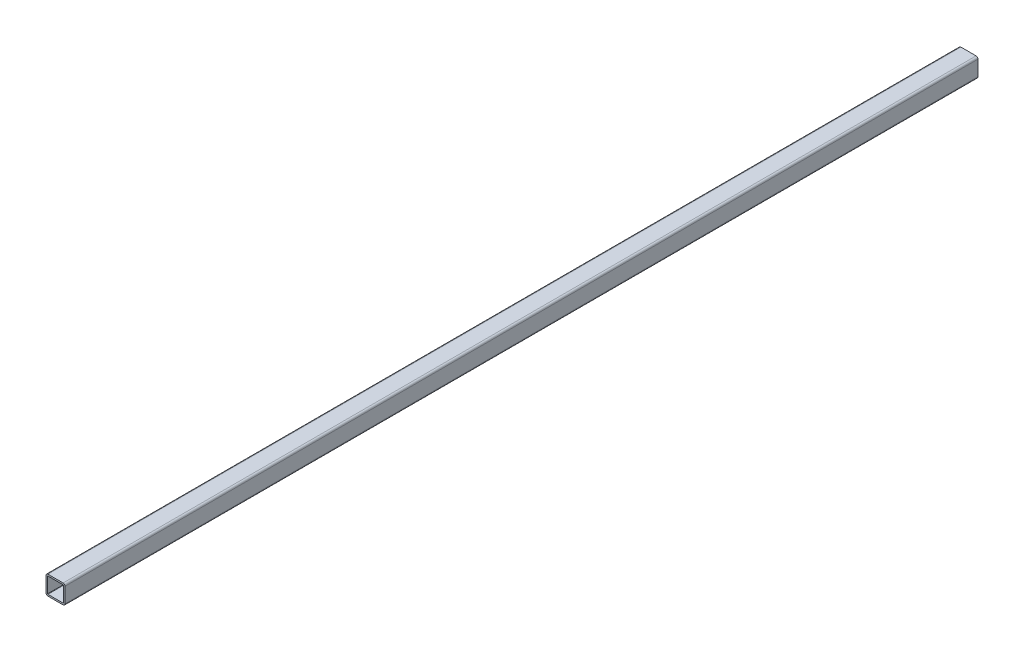
SolidWorks part; units mm, degrees
ref_plane "Front Plane" through (0, 0, 0) normal (0, 0, 1) x (1, 0, 0)
ref_plane "Top Plane" through (0, 0, 0) normal (0, 1, 0) x (1, 0, 0)
ref_plane "Right Plane" through (0, 0, 0) normal (1, 0, 0) x (0, 0, -1)
sketch "Sketch1" plane through (0, 0, 0) normal (0, 0, 1) x (1, 0, 0)
  line L0 (7.9375, -7.9375) -> (9.525, -7.9375) construction
  line L1 (-9.525, -9.525) -> (9.525, -9.525)
  line L2 (-9.525, -9.525) -> (-9.525, 9.525)
  line L3 (-9.525, 9.525) -> (9.525, 9.525)
  line L4 (9.525, -9.525) -> (9.525, 9.525)
  line L5 (0, 9.525) -> (0, -9.525) construction
  line L6 (-9.525, 0) -> (9.525, 0) construction
  line L7 (-7.9375, -7.9375) -> (7.9375, -7.9375)
  line L8 (-7.9375, -7.9375) -> (-7.9375, 7.9375)
  line L9 (-7.9375, 7.9375) -> (7.9375, 7.9375)
  line L10 (7.9375, -7.9375) -> (7.9375, 7.9375)
  line L11 (0, 7.9375) -> (0, -7.9375) construction
  line L12 (-7.9375, 0) -> (7.9375, 0) construction
  point P0 (0, 0)
  point P4 (0, 0)
  dimension "Outside Height" = 19.05
  dimension "Outside Width" = 19.05
  dimension "Inside Height" = 15.875
  dimension "Inside Width" = 15.875
  dimension "Wall Thickness" = 1.5875
sketch "Sketch3" plane through (0, 0, 0) normal (1, 0, 0) x (0, 0, -1)
  line L0 (-457.2, -9.525) -> (457.2, -9.525) construction
  point P2 (-431.8, -9.525)
  point P4 (431.8, -9.525)
  dimension "Length" = 914.4
  dimension "D1" = 25.4
  dimension "D2" = 25.4
sketch "Sketch2" plane through (0, 0, 0) normal (0, 0, 1) x (1, 0, 0)
  line L0 (-7.9375, -7.9375) -> (-7.9375, 7.9375) construction
  line L1 (-7.9375, -7.9375) -> (7.9375, -7.9375) construction
  line L2 (7.9375, -7.9375) -> (7.9375, 7.9375) construction
  line L3 (-7.9375, 7.9375) -> (7.9375, 7.9375) construction
  line L4 (-7.9375, -7.9375) -> (-7.9375, 7.9375)
  line L5 (-7.9375, -7.9375) -> (7.9375, -7.9375)
  line L6 (7.9375, -7.9375) -> (7.9375, 7.9375)
  line L7 (-7.9375, 7.9375) -> (7.9375, 7.9375)
  line L8 (-9.525, -9.525) -> (-9.525, 9.525) construction
  line L9 (-9.525, -9.525) -> (9.525, -9.525) construction
  line L10 (9.525, -9.525) -> (9.525, 9.525) construction
  line L11 (-9.525, 9.525) -> (9.525, 9.525) construction
  line L12 (-9.525, -9.525) -> (-9.525, 9.525)
  line L13 (-9.525, -9.525) -> (9.525, -9.525)
  line L14 (9.525, -9.525) -> (9.525, 9.525)
  line L15 (-9.525, 9.525) -> (9.525, 9.525)
extrude "Boss-Extrude1" add sketch "Sketch2" along normal mid plane 914.4
fillet "Fillet1" radius 1.905 4 edges at (-9.525, -9.525, 0) (-9.525, 9.525, 0) (9.525, -9.525, 0) (9.525, 9.525, 0)
fillet "Fillet2" radius 0.3175 4 edges at (7.9375, 7.9375, 0) (7.9375, -7.9375, 0) (-7.9375, -7.9375, 0) (-7.9375, 7.9375, 0)
equation "\"D1@Boss-Extrude1\"=\"length@sketch3\""
equation "\"D1@Fillet1\"=\"Wall Thickness@Sketch1\"*1.2"
equation "\"D1@Fillet2\"=\"D1@Fillet1\"-\"Wall Thickness@Sketch1\""
equation "\"D2@Sketch3\"=\"D1@Sketch3\""
